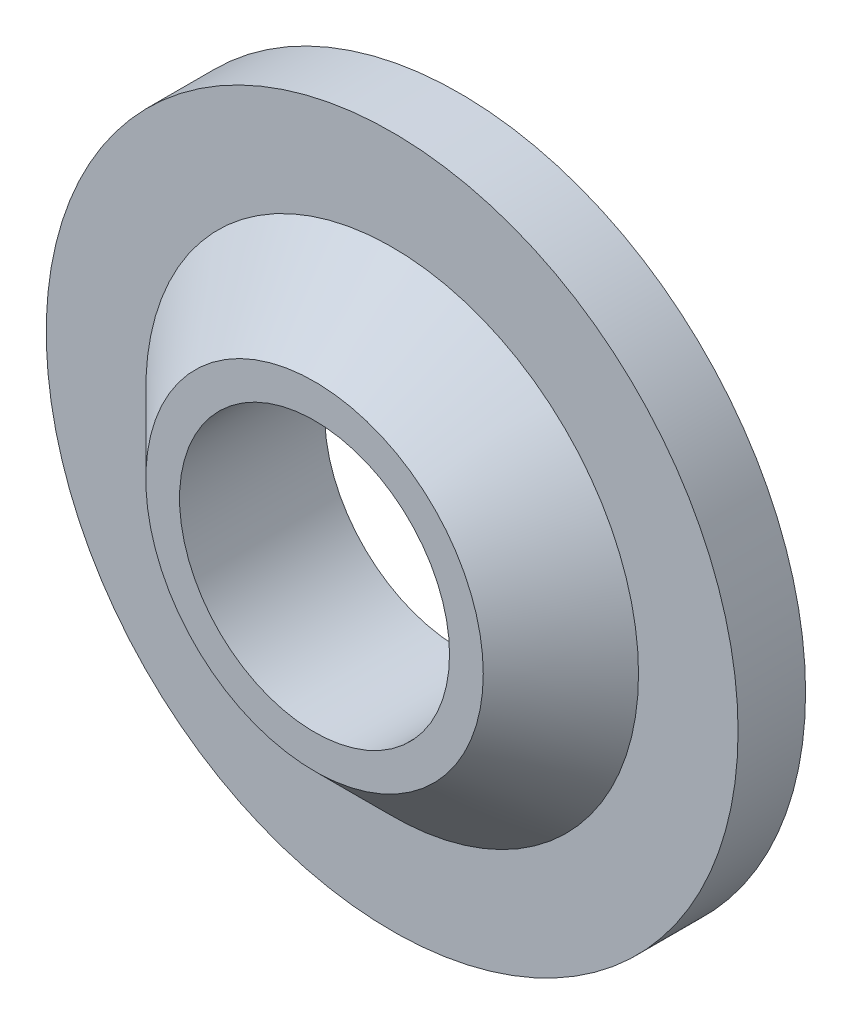
SolidWorks part; units mm, degrees
material "Alloy Steel"
ref_plane "X-Y Datum" through (0, 0, 0) normal (0, 0, 1) x (1, 0, 0)
ref_plane "X-Z Datum" through (0, 0, 0) normal (0, 1, 0) x (1, 0, 0)
ref_plane "Y-Z Datum" through (0, 0, 0) normal (1, 0, 0) x (0, 0, -1)
sketch "Sketch1" plane through (0, 0, 0) normal (0, 1, 0) x (1, 0, 0)
  line L0 (-10.25, 0) -> (-4, 0)
  line L1 (-4, 0) -> (-4, -4.3)
  line L2 (-4, -4.3) -> (-5, -4.3)
  line L3 (-5, -4.3) -> (-7.3, -2)
  line L4 (-7.3, -2) -> (-10.25, -2)
  line L5 (-10.25, -2) -> (-10.25, 0)
  line L6 (0, -37.8017) -> (0, 37.8017) construction
  dimension "D1" = 20.5
  dimension "D2" = 8
  dimension "D3" = 10
  dimension "D4" = 45
  dimension "D5" = 4.3
  dimension "D6" = 2
revolve "Revolve1" add sketch "Sketch1" angle 360 about L6
